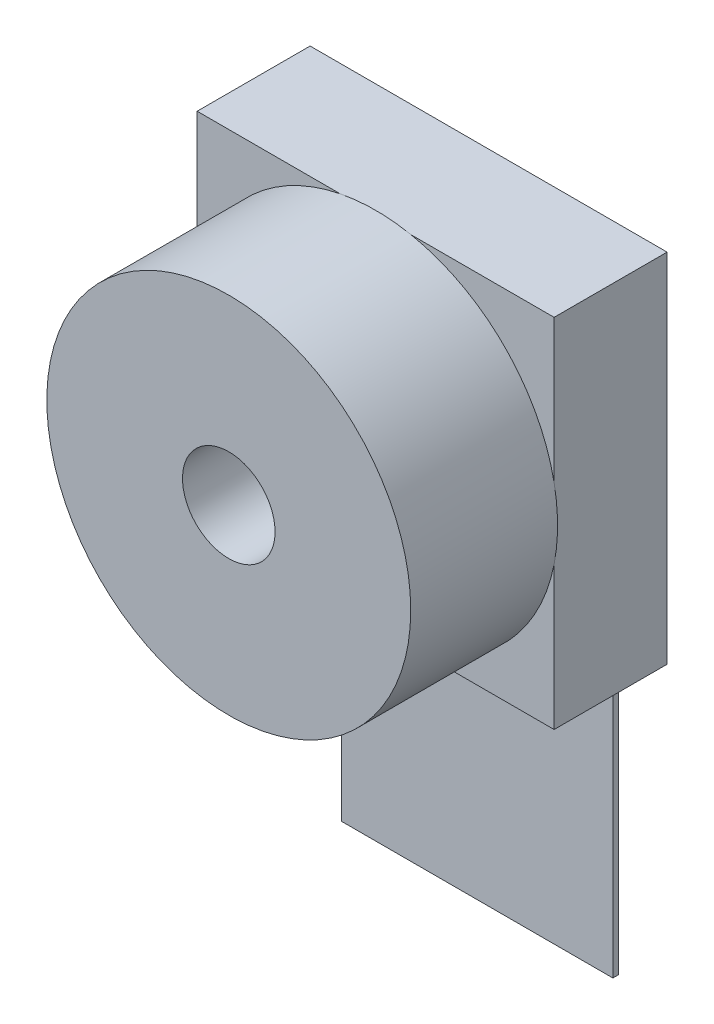
SolidWorks part; units mm, degrees
ref_plane "Front Plane" through (0, 0, 0) normal (0, 0, 1) x (1, 0, 0)
ref_plane "Top Plane" through (0, 0, 0) normal (0, 1, 0) x (1, 0, 0)
ref_plane "Right Plane" through (0, 0, 0) normal (1, 0, 0) x (0, 0, -1)
sketch "Sketch1" plane through (0, 0, 0) normal (0, 0, 1) x (1, 0, 0)
  line L1 (-4.0132, -4.0132) -> (4.0132, -4.0132)
  line L2 (-4.0132, -4.0132) -> (-4.0132, 4.0132)
  line L3 (-4.0132, 4.0132) -> (4.0132, 4.0132)
  line L4 (4.0132, -4.0132) -> (4.0132, 4.0132)
  line L5 (-4.0132, -4.0132) -> (4.0132, 4.0132) construction
  line L6 (-4.0132, 4.0132) -> (4.0132, -4.0132) construction
  point P0 (0, 0)
extrude "Boss-Extrude1" add sketch "Sketch1" along normal blind 2.286
sketch "Sketch2" plane through (0, 0, 2.286) normal (0, 0, 1) x (1, 0, 0)
  circle A0 centre (0, 0) radius 4.0913
extrude "Boss-Extrude2" add sketch "Sketch2" along normal blind 3.302
sketch "Sketch3" plane through (0, 0, 5.588) normal (0, 0, 1) x (1, 0, 0)
  circle A0 centre (0, 0) radius 1.0405
extrude "Cut-Extrude1" cut sketch "Sketch3" against normal blind 3.302
sketch "Sketch8" plane through (0, 0, 0) normal (0, 0, -1) x (-1, 0, 0)
  line L1 (-3.048, 3.048) -> (3.048, 3.048)
  line L2 (-3.048, 3.048) -> (-3.048, -10.4775)
  line L3 (-3.048, -10.4775) -> (3.048, -10.4775)
  line L4 (3.048, 3.048) -> (3.048, -10.4775)
extrude "Boss-Extrude6" add sketch "Sketch8" along normal blind 0.127
sketch "Sketch9" plane through (0, 0, 0) normal (0, 0, -1) x (-1, 0, 0)
  line L1 (-4.0132, 4.0132) -> (4.0132, 4.0132)
  line L2 (-4.0132, 4.0132) -> (-4.0132, -4.0132)
  line L3 (-4.0132, -4.0132) -> (4.0132, -4.0132)
  line L4 (4.0132, 4.0132) -> (4.0132, -4.0132)
extrude "Boss-Extrude7" add sketch "Sketch9" along normal blind 0.254
sketch "Sketch11" plane through (0, 0, -0.254) normal (0, 0, -1) x (-1, 0, 0)
  line L2 (1.6677, 5.1503) -> (1.9002, 5.1503)
  line L3 (1.9002, 5.1503) -> (1.9002, 6.4226)
  line L4 (1.6677, 5.1503) -> (1.6677, 6.4226)
  text T0 "UP ^\r\n" font "Century Gothic" height in points 8
